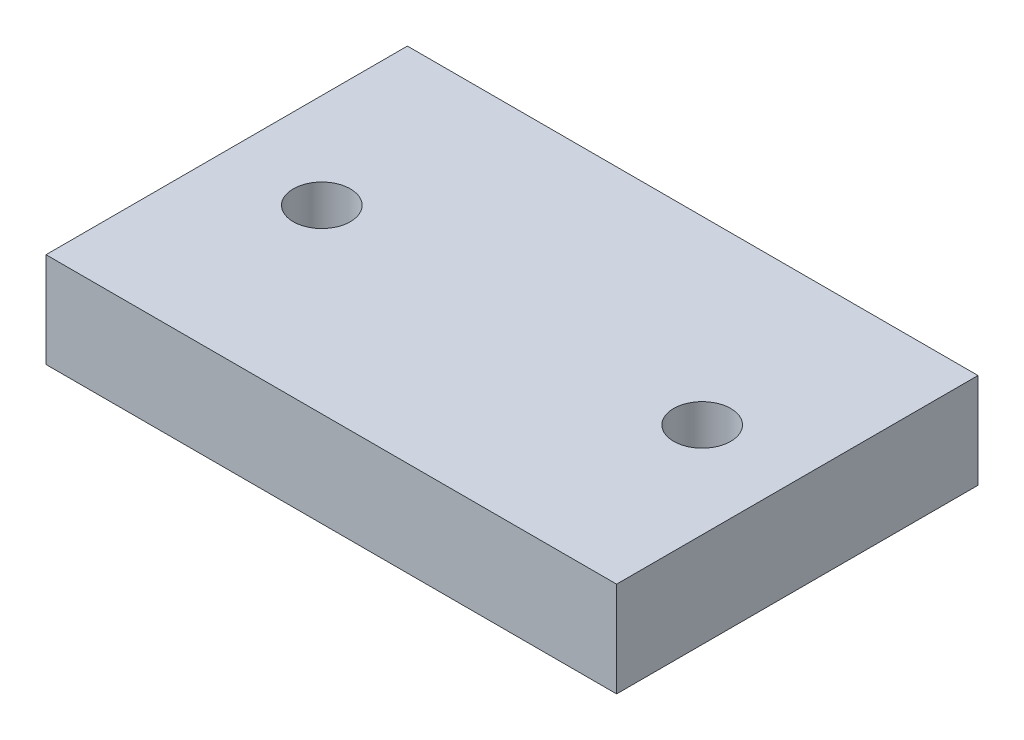
SolidWorks part; units mm, degrees
ref_plane "Front Plane" through (0, 0, 0) normal (0, 0, 1) x (1, 0, 0)
ref_plane "Top Plane" through (0, 0, 0) normal (0, 1, 0) x (1, 0, 0)
ref_plane "Right Plane" through (0, 0, 0) normal (1, 0, 0) x (0, 0, -1)
sketch "Sketch1" plane through (0, 0, 0) normal (0, 1, 0) x (1, 0, 0)
  line L0 (0, 9.5) -> (30, 9.5) construction
  line L1 (0, 0) -> (30, 0)
  line L2 (0, 0) -> (0, 19)
  line L3 (0, 19) -> (30, 19)
  line L4 (30, 0) -> (30, 19)
  line L5 (15, 19) -> (15, 0) construction
  circle A0 centre (5, 9.5) radius 1.5
  circle A1 centre (25, 9.5) radius 1.5
  dimension "D3" = 3
  dimension "D4" = 10
  dimension "D1" = 19
  dimension "D2" = 30
extrude "Boss-Extrude1" add sketch "Sketch1" along normal mid plane 5
